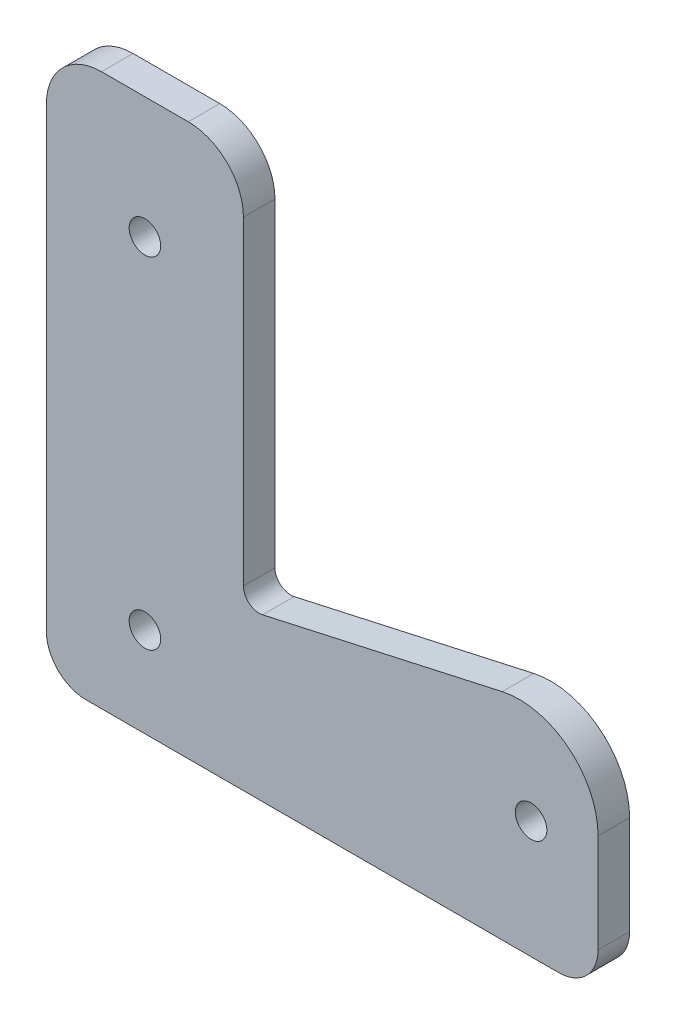
SolidWorks part; units mm, degrees
ref_plane "Piano frontale" through (0, 0, 0) normal (0, 0, 1) x (1, 0, 0)
ref_plane "Piano superiore" through (0, 0, 0) normal (0, 1, 0) x (1, 0, 0)
ref_plane "Piano destro" through (0, 0, 0) normal (1, 0, 0) x (0, 0, -1)
sketch "Schizzo1" plane through (0, 0, 0) normal (0, 0, 1) x (1, 0, 0)
  line L0 (0, 0) -> (0, 70)
  line L1 (0, 70) -> (25, 70)
  line L2 (25, 70) -> (25, 20)
  line L3 (25, 20) -> (70, 30)
  line L4 (70, 30) -> (70, 0)
  line L5 (70, 0) -> (0, 0)
  circle A0 centre (12.5, 11.4) radius 2
  circle A2 centre (12.5, 54.6) radius 2
  circle A3 centre (61.5, 14.9) radius 2
  point P13 (12.5, 70)
  dimension "D1" = 4
  dimension "D2" = 4
  dimension "D12" = 4
  dimension "D3" = 70
  dimension "D4" = 25
  dimension "D5" = 43.2
  dimension "D6" = 70
  dimension "D7" = 30
  dimension "D8" = 11.4
  dimension "D9" = 49
  dimension "D10" = 3.5
  dimension "D11" = 50
extrude "Estrusione-Estrusione1" add sketch "Schizzo1" along normal blind 4
fillet "Raccordo1" radius 7 2 edges at (25, 70, 2) (0, 70, 2)
fillet "Raccordo2" radius 5 2 edges at (70, 0, 2) (0, 0, 2)
fillet "Raccordo3" radius 10 1 edges at (70, 30, 2)
fillet "Raccordo4" radius 2 1 edges at (25, 20, 2)
